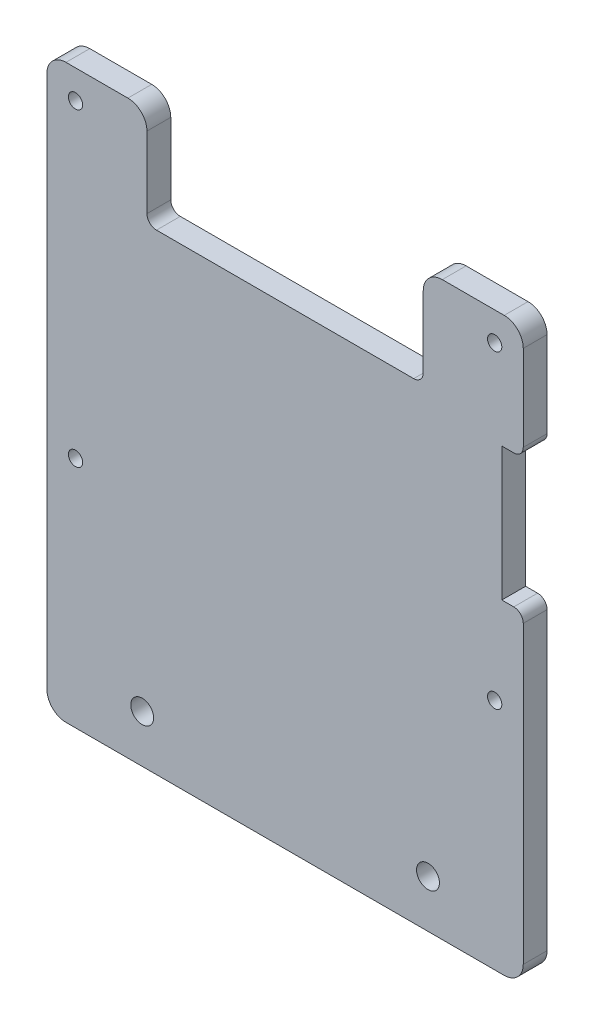
SolidWorks part; units mm, degrees
ref_plane "Front Plane" through (0, 0, 0) normal (0, 0, 1) x (1, 0, 0)
ref_plane "Top Plane" through (0, 0, 0) normal (0, 1, 0) x (1, 0, 0)
ref_plane "Right Plane" through (0, 0, 0) normal (1, 0, 0) x (0, 0, -1)
sketch "Sketch1" plane through (0, 0, 0) normal (0, 0, 1) x (1, 0, 0)
  line L0 (-65.9688, -40) -> (74.1879, -40) construction
  line L1 (-50, -60) -> (50, -60)
  line L2 (-50, -60) -> (-50, 60)
  line L3 (-50, 60) -> (-29, 60)
  line L4 (50, -60) -> (50, 8)
  line L5 (-50, -60) -> (50, 60) construction
  line L6 (-50, 60) -> (50, -60) construction
  line L7 (-65.9688, -50) -> (74.1879, -50) construction
  line L8 (0, 104.2323) -> (0, -102.2123) construction
  line L9 (-44, 85.5038) -> (-44, -72.8255) construction
  line L10 (44, 85.5038) -> (44, -65.6145) construction
  line L11 (-65.9688, 54) -> (70.5256, 54) construction
  line L12 (-65.9688, -11) -> (74.1879, -11) construction
  line L13 (-29, 60) -> (-29, 39)
  line L14 (-29, 39) -> (29, 39)
  line L15 (29, 39) -> (29, 60)
  line L16 (45.5, 36) -> (45.5, 8)
  line L17 (45.5, 36) -> (50, 36)
  line L18 (45.5, 8) -> (50, 8)
  line L19 (29, 60) -> (50, 60)
  line L20 (50, 36) -> (50, 60)
  circle A0 centre (-30, -50) radius 2.4
  circle A1 centre (30, -50) radius 2.4
  circle A2 centre (-44, 54) radius 1.5
  circle A3 centre (44, 54) radius 1.5
  circle A4 centre (-44, -11) radius 1.5
  circle A5 centre (44, -11) radius 1.5
  point P0 (0, 0)
  point P38 (50, 42.4566)
  dimension "D5" = 4.8
  dimension "D6" = 30
  dimension "D7" = 30
  dimension "D12" = 3
  dimension "D1" = 100
  dimension "D2" = 120
  dimension "D3" = 20
  dimension "D4" = 10
  dimension "D8" = 44
  dimension "D9" = 44
  dimension "D10" = 6
  dimension "D11" = 65
  dimension "D13" = 15
  dimension "D14" = 15
  dimension "D15" = 21
  dimension "D16" = 3
  dimension "D17" = 18
  dimension "D18" = 28
extrude "Boss-Extrude1" add sketch "Sketch1" along normal blind 5
fillet "Fillet1" radius 4 6 edges at (29, 60, 2.5) (-29, 60, 2.5) (50, -60, 2.5) (-50, -60, 2.5) (50, 60, 2.5) (-50, 60, 2.5)
fillet "Fillet2" radius 2 4 edges at (50, 8, 2.5) (50, 36, 2.5) (29, 39, 2.5) (-29, 39, 2.5)
